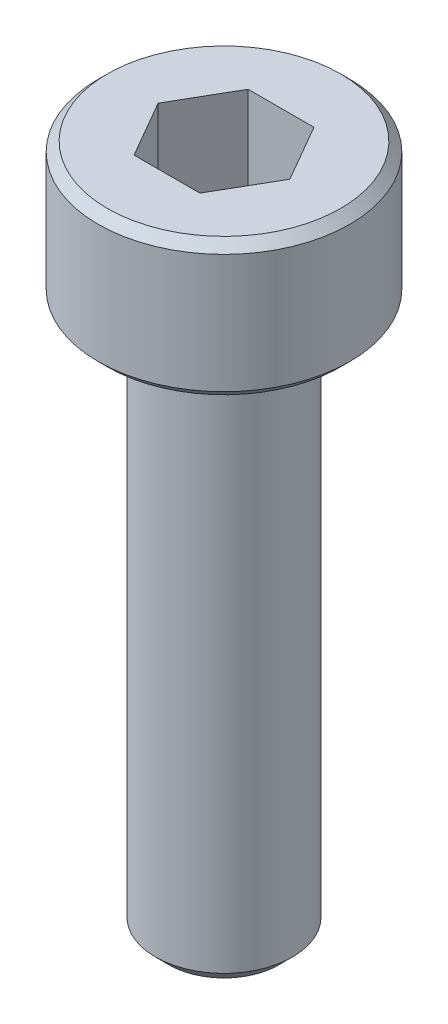
SolidWorks part; units mm, degrees
material "AISI 304"
ref_plane "前视基准面" through (0, 0, 0) normal (0, 0, 1) x (1, 0, 0)
ref_plane "上视基准面" through (0, 0, 0) normal (0, 1, 0) x (1, 0, 0)
ref_plane "右视基准面" through (0, 0, 0) normal (1, 0, 0) x (0, 0, -1)
sketch "草图1" plane through (0, 0, 0) normal (0, 0, 1) x (1, 0, 0)
  line L0 (1.5, 0) -> (2.75, 0)
  line L1 (2.75, 0) -> (2.75, 3)
  line L2 (2.75, 3) -> (0, 3)
  line L3 (0, 3) -> (0, 0)
  line L4 (1.5, 0) -> (1.5, -12)
  line L5 (1.5, -12) -> (0, -12)
  line L6 (0, -12) -> (0, 0)
  dimension "D1" = 3
  dimension "D2" = 2.75
  dimension "D3" = 1.5
  dimension "D4" = 12
  dimension "D5" = 2.75
revolve "旋转1" add sketch "草图1" angle 360 about L3
chamfer "倒角1" distance 0.2 angle 45 2 edges at (0, 0, 2.75) (0, 3, 2.75)
chamfer "倒角2" distance 0.3 angle 45 1 edges at (0, -12, 1.5)
sketch "草图2" plane through (0, 3, 0) normal (0, 1, 0) x (1, 0, 0)
  line L0 (-0.72, 1.2471) -> (0.72, 1.2471)
  line L1 (0.72, 1.2471) -> (1.44, 0)
  line L2 (1.44, 0) -> (0.72, -1.2471)
  line L3 (0.72, -1.2471) -> (-0.72, -1.2471)
  line L4 (-0.72, -1.2471) -> (-1.44, 0)
  line L5 (-1.44, 0) -> (-0.72, 1.2471)
extrude "切除-拉伸1" cut sketch "草图2" against normal blind 2.5
